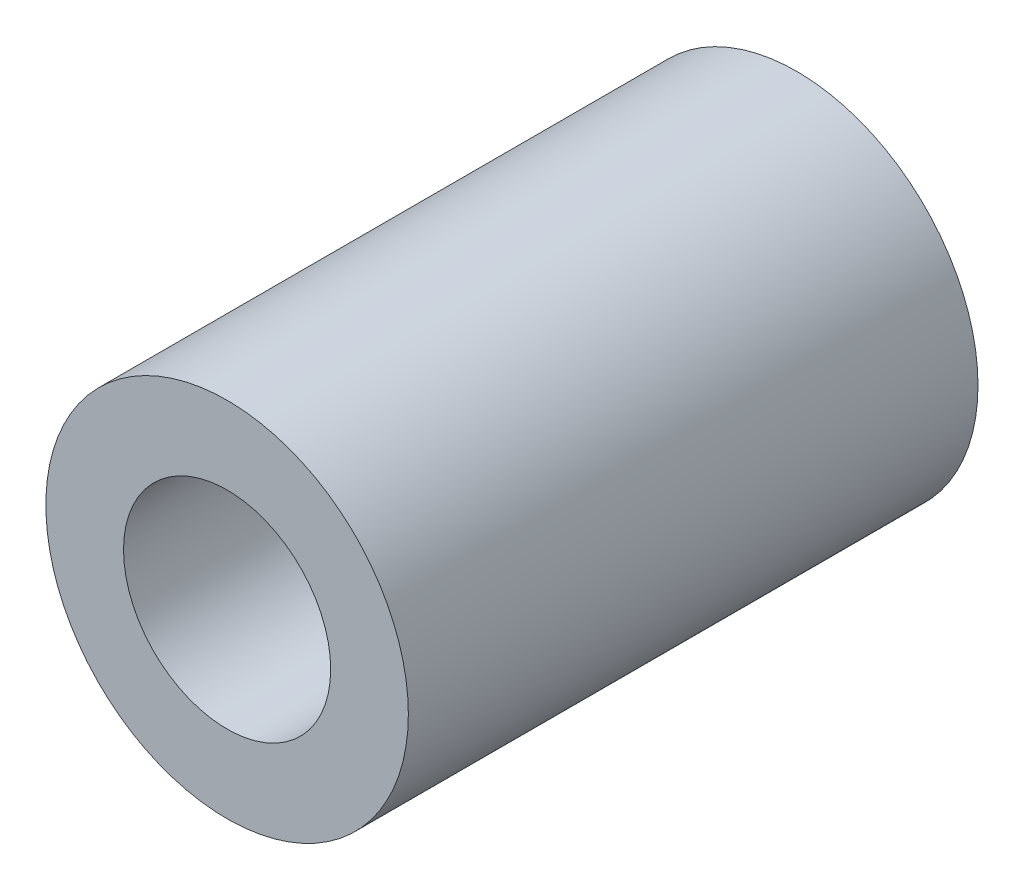
SolidWorks part; units mm, degrees
material "Nylon 101"
ref_plane "Front Plane" through (0, 0, 0) normal (0, 0, 1) x (1, 0, 0)
ref_plane "Top Plane" through (0, 0, 0) normal (0, 1, 0) x (1, 0, 0)
ref_plane "Right Plane" through (0, 0, 0) normal (1, 0, 0) x (0, 0, -1)
sketch "Sketch1" plane through (0, 0, 0) normal (0, 0, 1) x (1, 0, 0)
  circle A0 centre (0, 0) radius 2
  circle A1 centre (0, 0) radius 3.5
  dimension "D1" = 7
  dimension "D2" = 4
extrude "Boss-Extrude1" add sketch "Sketch1" along normal blind 11
